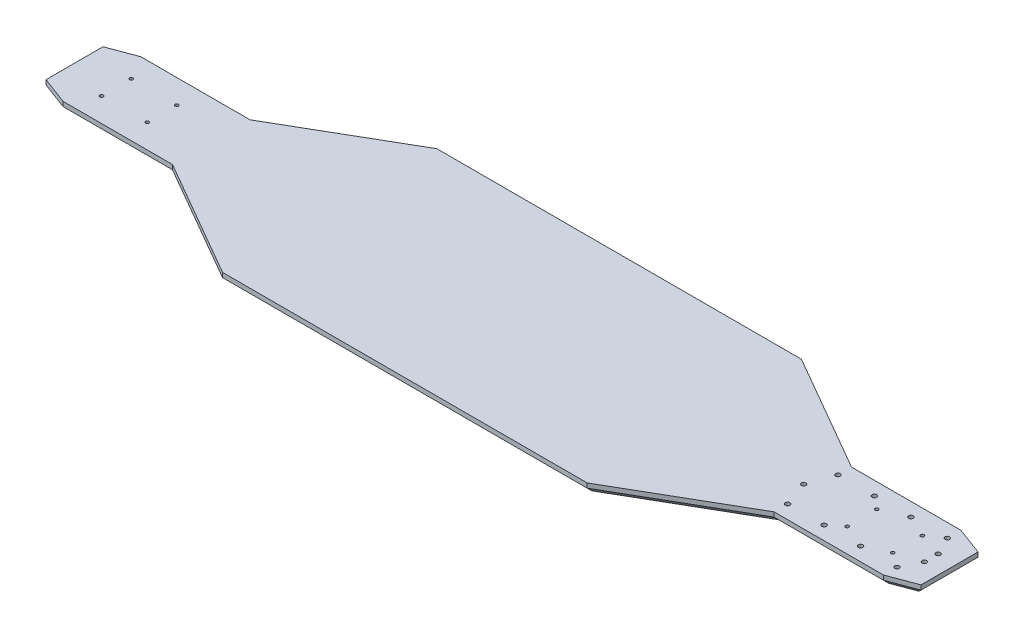
SolidWorks part; units mm, degrees
ref_plane "Front Plane" through (0, 0, 0) normal (0, 0, 1) x (1, 0, 0)
ref_plane "Top Plane" through (0, 0, 0) normal (0, 1, 0) x (1, 0, 0)
ref_plane "Right Plane" through (0, 0, 0) normal (1, 0, 0) x (0, 0, -1)
sketch "Sketch1" plane through (0, 0, 0) normal (0, 1, 0) x (1, 0, 0)
  line L0 (-241.1419, 54.734) -> (368.336, 54.734) construction
  line L1 (-241.1419, 15.0465) -> (-241.1419, 94.4215)
  line L2 (114.336, -94.491) -> (368.336, -94.491)
  line L3 (368.336, -94.491) -> (368.336, 54.734) construction
  line L4 (-50.6419, 108.709) -> (114.336, 203.959)
  line L5 (-203.0419, 108.709) -> (-241.1419, 94.4215)
  line L6 (-203.0419, 108.709) -> (-50.6419, 108.709)
  line L7 (-203.0419, 0.759) -> (-50.6419, 0.759)
  line L8 (114.336, 203.959) -> (368.336, 203.959)
  line L9 (787.3138, 0.759) -> (622.336, -94.491)
  line L10 (-203.0419, 0.759) -> (-241.1419, 15.0465)
  line L11 (-50.6419, 0.759) -> (114.336, -94.491)
  line L12 (939.7138, 0.759) -> (977.8138, 15.0465)
  line L13 (622.336, 203.959) -> (368.336, 203.959)
  line L14 (939.7138, 0.759) -> (787.3138, 0.759)
  line L15 (939.7138, 108.709) -> (787.3138, 108.709)
  line L16 (939.7138, 108.709) -> (977.8138, 94.4215)
  line L17 (787.3138, 108.709) -> (622.336, 203.959)
  line L18 (622.336, -94.491) -> (368.336, -94.491)
  line L19 (977.8138, 15.0465) -> (977.8138, 94.4215)
  dimension "D9" = 355.4778
  dimension "D2" = 149.225
  dimension "D3" = 152.4
  dimension "D4" = 38.1
  dimension "D5" = 254
  dimension "D6" = 79.375
  dimension "D7" = 150
  dimension "D8" = 14.2875
  dimension "D10" = 190.5
  dimension "D11" = 190.5
  dimension "D12" = 107.95
  dimension "D13" = 53.975
  dimension "D14" = 149.225
  dimension "D15" = 39.6875
extrude "Boss-Extrude1" add sketch "Sketch1" along normal blind 15.24
sketch "Sketch2" plane through (0, 0, 0) normal (0, -1, 0) x (-1, 0, 0)
  line L0 (241.1419, 54.734) -> (-37.1273, 54.734) construction
  line L1 (241.1419, 94.4215) -> (241.1419, 15.0465) construction
  line L2 (-368.336, -94.491) -> (-368.336, 203.959) construction
  line L3 (-114.336, -94.491) -> (-622.336, -94.491) construction
  line L4 (-622.336, 203.959) -> (-114.336, 203.959) construction
  line L5 (119.2219, 75.3715) -> (119.2219, 34.0965) construction
  line L6 (119.2219, 34.0965) -> (182.7219, 34.0965) construction
  line L7 (182.7219, 34.0965) -> (182.7219, 75.3715) construction
  line L8 (182.7219, 75.3715) -> (119.2219, 75.3715) construction
  circle A0 centre (182.7219, 34.0965) radius 2.3813
  circle A1 centre (182.7219, 75.3715) radius 2.3813
  circle A2 centre (119.2219, 75.3715) radius 2.3812
  circle A3 centre (119.2219, 34.0965) radius 2.3813
  circle A4 centre (-855.8938, 75.3715) radius 2.3813
  circle A5 centre (-919.3938, 75.3715) radius 2.3812
  circle A6 centre (-919.3938, 34.0965) radius 2.3812
  circle A7 centre (-855.8938, 34.0965) radius 2.3812
  point P29 (50.6419, 108.709)
  dimension "D1" = 58.42
  dimension "D2" = 63.5
  dimension "D3" = 41.275
  dimension "D4" = 20.6375
extrude "Cut-Extrude1" cut sketch "Sketch2" against normal blind 15.24
chamfer "Chamfer1" distance 8.89 angle 45 16 edges at (-126.8419, 0, -0.759) (-222.0919, 0, -7.9028) (-241.1419, 0, -54.734) (-222.0919, 0, -101.5653) (-126.8419, 0, -108.709) (31.8471, 0, -156.334) (31.8471, 0, 46.866) (368.336, 0, 94.491) (704.8249, 0, 46.866) (863.5138, 0, -0.759) (958.7638, 0, -7.9028) (977.8138, 0, -54.734) (958.7638, 0, -101.5653) (863.5138, 0, -108.709) (704.8249, 0, -156.334) (368.336, 0, -203.959)
sketch "Sketch3" plane through (0, 0, 0) normal (0, -1, 0) x (1, 0, 0)
  line L0 (654.086, -105.534) -> (717.586, -105.534)
  line L1 (938.1018, -9.649) -> (784.9318, -9.649) construction
  line L2 (377.861, -181.734) -> (377.861, 72.266) construction
  line L3 (419.136, -169.034) -> (419.136, 59.566)
  line L4 (114.336, 72.266) -> (114.336, -181.734) construction
  line L5 (419.136, -54.734) -> (609.636, -54.734) construction
  line L6 (514.386, -54.734) -> (514.386, -169.034) construction
  line L7 (546.136, -156.334) -> (482.636, -156.334) construction
  line L8 (546.136, -105.534) -> (482.636, -105.534) construction
  line L9 (482.636, -105.534) -> (482.636, -156.334) construction
  line L10 (631.861, -133.069) -> (631.861, 46.866) construction
  line L11 (546.136, -105.534) -> (546.136, -156.334) construction
  line L12 (654.086, -3.934) -> (717.586, -3.934)
  line L13 (654.086, -3.934) -> (654.086, -105.534)
  line L14 (717.586, -105.534) -> (717.586, -3.934)
  line L15 (609.636, -54.734) -> (792.0003, -54.734) construction
  line L16 (641.386, -123.4498) -> (641.386, 24.6279) construction
  line L17 (641.386, -118.234) -> (730.286, -118.234) construction
  line L18 (730.286, -118.234) -> (730.286, 8.766) construction
  line L19 (730.286, 8.766) -> (641.386, 8.766) construction
  line L20 (419.136, -54.734) -> (390.561, -54.734) construction
  line L21 (404.8485, -169.034) -> (404.8485, 59.566) construction
  line L22 (685.836, -118.234) -> (685.836, 8.766) construction
  line L23 (500.0985, -169.034) -> (500.0985, 59.566) construction
  line L24 (236.5735, -169.034) -> (236.5735, 59.566) construction
  line L25 (50.836, -118.234) -> (50.836, 8.766) construction
  line L26 (331.8235, -169.034) -> (331.8235, 59.566) construction
  line L27 (317.536, -54.734) -> (346.111, -54.734) construction
  line L28 (6.386, 8.766) -> (95.286, 8.766) construction
  line L29 (6.386, -118.234) -> (6.386, 8.766) construction
  line L30 (95.286, -118.234) -> (6.386, -118.234) construction
  line L31 (95.286, -123.4498) -> (95.286, 24.6279) construction
  line L32 (127.036, -54.734) -> (-55.3283, -54.734) construction
  line L33 (190.536, -105.534) -> (190.536, -156.334) construction
  line L34 (104.811, -133.069) -> (104.811, 46.866) construction
  line L35 (254.036, -105.534) -> (254.036, -156.334) construction
  line L36 (190.536, -105.534) -> (254.036, -105.534) construction
  line L37 (368.336, -181.734) -> (368.336, 72.266) construction
  line L38 (190.536, -156.334) -> (254.036, -156.334) construction
  line L39 (222.286, -54.734) -> (222.286, -169.034) construction
  line L40 (622.336, 72.266) -> (622.336, -181.734) construction
  line L41 (317.536, -54.734) -> (127.036, -54.734) construction
  line L42 (358.811, -181.734) -> (358.811, 72.266) construction
  line L43 (-44.6867, -22.984) -> (120.2912, 72.266)
  line L44 (-199.8669, -22.984) -> (-44.6867, -22.984)
  line L45 (609.636, -169.034) -> (390.561, -169.034)
  line L46 (609.636, -169.034) -> (609.636, 59.566)
  line L47 (609.636, 59.566) -> (390.561, 59.566)
  line L48 (390.561, -169.034) -> (390.561, 59.566)
  line L49 (-218.9169, -30.4485) -> (-199.8669, -22.984)
  line L50 (-218.9169, -79.0196) -> (-218.9169, -30.4485)
  line L51 (-199.0117, -86.484) -> (-218.9169, -79.0196)
  line L52 (-44.6867, -86.484) -> (-199.0117, -86.484)
  line L53 (120.2912, -181.734) -> (-44.6867, -86.484)
  line L54 (346.111, -169.034) -> (346.111, 59.566)
  line L55 (127.036, 59.566) -> (346.111, 59.566)
  line L56 (127.036, -169.034) -> (127.036, 59.566)
  line L57 (127.036, -169.034) -> (346.111, -169.034)
  line L58 (19.086, -105.534) -> (19.086, -3.934)
  line L59 (82.586, -3.934) -> (82.586, -105.534)
  line L60 (82.586, -3.934) -> (19.086, -3.934)
  line L61 (317.536, -169.034) -> (317.536, 59.566)
  line L62 (82.586, -105.534) -> (19.086, -105.534)
  line L63 (955.5888, -79.0196) -> (936.5388, -79.0196) construction
  line L64 (936.5388, -79.0196) -> (936.5388, -30.4485) construction
  line L65 (936.5388, -30.4485) -> (955.5888, -30.4485) construction
  line L66 (968.9238, -88.2607) -> (968.9238, -21.2073) construction
  line L76 (616.3808, -181.734) -> (781.3587, -86.484)
  line L77 (781.3587, -86.484) -> (935.6837, -86.484)
  line L78 (935.6837, -86.484) -> (955.5888, -79.0196)
  line L79 (955.5888, -79.0196) -> (955.5888, -30.4485)
  line L80 (955.5888, -30.4485) -> (936.5388, -22.984)
  line L81 (936.5388, -22.984) -> (781.3587, -22.984)
  line L82 (781.3587, -22.984) -> (616.3808, 72.266)
  circle A0 centre (358.811, 46.866) radius 3.175
  circle A1 centre (546.136, -156.334) radius 3.175
  circle A2 centre (482.636, -156.334) radius 3.175
  circle A4 centre (546.136, -105.534) radius 3.175
  circle A5 centre (358.811, -3.934) radius 3.175
  circle A6 centre (482.636, -105.534) radius 3.175
  circle A7 centre (546.136, -80.134) radius 3.175
  circle A8 centre (546.136, -29.334) radius 3.175
  circle A9 centre (482.636, -29.334) radius 3.175
  circle A10 centre (482.636, -80.134) radius 3.175
  circle A11 centre (546.136, -3.934) radius 3.175
  circle A12 centre (546.136, 46.866) radius 3.175
  circle A13 centre (482.636, 46.866) radius 3.175
  circle A14 centre (482.636, -3.934) radius 3.175
  circle A15 centre (730.286, -54.734) radius 3.175
  circle A16 centre (730.286, -105.534) radius 3.175
  circle A17 centre (730.286, -3.934) radius 3.175
  circle A18 centre (711.236, 8.766) radius 3.175
  circle A19 centre (660.436, 8.766) radius 3.175
  circle A20 centre (622.336, -156.334) radius 3.175
  circle A21 centre (404.8485, -156.334) radius 3.175
  circle A22 centre (404.8485, -105.534) radius 3.175
  circle A23 centre (404.8485, -54.734) radius 3.175
  circle A24 centre (404.8485, -3.934) radius 3.175
  circle A25 centre (404.8485, 46.866) radius 3.175
  circle A26 centre (660.436, -118.234) radius 3.175
  circle A27 centre (711.236, -118.234) radius 3.175
  circle A28 centre (641.386, -105.534) radius 3.175
  circle A29 centre (641.386, -54.734) radius 3.175
  circle A30 centre (641.386, -3.934) radius 3.175
  circle A31 centre (622.336, -105.534) radius 3.175
  circle A32 centre (622.336, -54.734) radius 3.175
  circle A33 centre (622.336, -3.934) radius 3.175
  circle A34 centre (622.336, 46.866) radius 3.175
  circle A35 centre (601.6985, -181.734) radius 3.175
  circle A36 centre (550.8985, -181.734) radius 3.175
  circle A37 centre (500.0985, -181.734) radius 3.175
  circle A38 centre (449.2985, -181.734) radius 3.175
  circle A39 centre (398.4985, -181.734) radius 3.175
  circle A40 centre (398.4985, 72.266) radius 3.175
  circle A41 centre (449.2985, 72.266) radius 3.175
  circle A42 centre (500.0985, 72.266) radius 3.175
  circle A43 centre (550.8985, 72.266) radius 3.175
  circle A44 centre (601.6985, 72.266) radius 3.175
  circle A45 centre (377.861, -156.334) radius 3.175
  circle A46 centre (377.861, -105.534) radius 3.175
  circle A47 centre (377.861, -54.734) radius 3.175
  circle A48 centre (377.861, -3.934) radius 3.175
  circle A49 centre (377.861, 46.866) radius 3.175
  circle A50 centre (358.811, -54.734) radius 3.175
  circle A51 centre (358.811, -105.534) radius 3.175
  circle A52 centre (358.811, -156.334) radius 3.175
  circle A53 centre (134.9735, 72.266) radius 3.175
  circle A54 centre (185.7735, 72.266) radius 3.175
  circle A55 centre (236.5735, 72.266) radius 3.175
  circle A56 centre (287.3735, 72.266) radius 3.175
  circle A57 centre (338.1735, 72.266) radius 3.175
  circle A58 centre (338.1735, -181.734) radius 3.175
  circle A59 centre (287.3735, -181.734) radius 3.175
  circle A60 centre (236.5735, -181.734) radius 3.175
  circle A61 centre (185.7735, -181.734) radius 3.175
  circle A62 centre (134.9735, -181.734) radius 3.175
  circle A63 centre (114.336, 46.866) radius 3.175
  circle A64 centre (114.336, -3.934) radius 3.175
  circle A65 centre (114.336, -54.734) radius 3.175
  circle A66 centre (114.336, -105.534) radius 3.175
  circle A67 centre (95.286, -3.934) radius 3.175
  circle A68 centre (95.286, -54.734) radius 3.175
  circle A69 centre (95.286, -105.534) radius 3.175
  circle A70 centre (25.436, -118.234) radius 3.175
  circle A71 centre (76.236, -118.234) radius 3.175
  circle A72 centre (331.8235, 46.866) radius 3.175
  circle A73 centre (331.8235, -3.934) radius 3.175
  circle A74 centre (331.8235, -54.734) radius 3.175
  circle A75 centre (331.8235, -105.534) radius 3.175
  circle A76 centre (331.8235, -156.334) radius 3.175
  circle A77 centre (114.336, -156.334) radius 3.175
  circle A78 centre (76.236, 8.766) radius 3.175
  circle A79 centre (25.436, 8.766) radius 3.175
  circle A80 centre (6.386, -3.934) radius 3.175
  circle A81 centre (6.386, -105.534) radius 3.175
  circle A82 centre (6.386, -54.734) radius 3.175
  circle A83 centre (254.036, -3.934) radius 3.175
  circle A84 centre (254.036, 46.866) radius 3.175
  circle A85 centre (190.536, 46.866) radius 3.175
  circle A86 centre (190.536, -3.934) radius 3.175
  circle A87 centre (254.036, -80.134) radius 3.175
  circle A88 centre (254.036, -29.334) radius 3.175
  circle A89 centre (190.536, -29.334) radius 3.175
  circle A90 centre (190.536, -80.134) radius 3.175
  circle A91 centre (254.036, -105.534) radius 3.175
  circle A92 centre (190.536, -105.534) radius 3.175
  circle A93 centre (254.036, -156.334) radius 3.175
  circle A94 centre (190.536, -156.334) radius 3.175
  circle A95 centre (0, 0) radius 2.7305
  circle A99 centre (-218.9169, -79.0196) radius 2.7305
  circle A100 centre (-199.8669, -79.0196) radius 2.7305
  circle A101 centre (-199.8669, -30.4485) radius 2.7305
  circle A102 centre (-218.9169, -30.4485) radius 2.7305
  circle A103 centre (936.5388, -29.334) radius 3.175
  circle A104 centre (936.5388, -80.134) radius 3.175
  circle A105 centre (955.5888, -80.134) radius 3.175
  circle A106 centre (955.5888, -29.334) radius 3.175
  point P48 (114.336, -203.959)
  point P276 (114.336, 94.491)
  point P302 (955.5888, -54.734)
  dimension "D7" = 6.35
  dimension "D13" = 31.75
  dimension "D20" = 3
  dimension "D39" = 5
  dimension "D5" = 6.35
  dimension "D8" = 6.35
  dimension "D11" = 6.35
  dimension "D12" = 6.35
  dimension "D14" = 50.8
  dimension "D15" = 25.4
  dimension "D43" = 6.35
  dimension "D44" = 6.35
  dimension "D45" = 6.35
  dimension "D46" = 6.35
  dimension "D47" = 6.35
  dimension "D48" = 6.35
  dimension "D49" = 6.35
  dimension "D50" = 6.35
  dimension "D51" = 6.35
  dimension "D52" = 6.35
  dimension "D53" = 6.35
  dimension "D54" = 6.35
  dimension "D3" = 254
  dimension "D6" = 9.525
  dimension "D9" = 219.075
  dimension "D10" = 190.5
  dimension "D16" = 31.75
  dimension "D17" = 13.335
  dimension "D18" = 12.7
  dimension "D19" = 50.8
  dimension "D21" = 12.7
  dimension "D22" = 101.6
  dimension "D23" = 63.5
  dimension "D24" = 22.225
  dimension "D25" = 12.7
  dimension "D26" = 50.8
  dimension "D27" = 12.7
  dimension "D28" = 12.7
  dimension "D29" = 12.7
  dimension "D30" = 19.05
  dimension "D31" = 50.8
  dimension "D32" = 50.8
  dimension "D33" = 50.8
  dimension "D34" = 12.7
  dimension "D35" = 25.4
  dimension "D36" = 20.6375
  dimension "D37" = 25.4
  dimension "D38" = 5
  dimension "D41" = 19.05
  dimension "D42" = 13.335
  dimension "D40" = 5
extrude "Cut-Extrude2" cut sketch "Sketch3" against normal blind 7.9375
sketch "Sketch4" plane through (0, 15.24, 0) normal (0, 1, 0) x (1, 0, 0)
  line L0 (977.8138, 15.0465) -> (977.8138, 94.4215) construction
  line L1 (977.8138, 89.659) -> (774.6138, 89.659)
  line L2 (977.8138, 89.659) -> (977.8138, 19.809)
  line L3 (977.8138, 19.809) -> (774.6138, 19.809)
  line L4 (774.6138, 89.659) -> (774.6138, 19.809)
  line L5 (952.4138, 89.659) -> (952.4138, 19.809) construction
  line L6 (774.6138, 54.734) -> (977.8138, 54.734) construction
  circle A0 centre (888.9138, 89.7619) radius 3.175
  circle A1 centre (952.4138, 45.209) radius 3.175
  circle A2 centre (939.7138, 89.7619) radius 3.175
  circle A3 centre (939.7138, 19.7061) radius 3.175
  circle A4 centre (888.9138, 19.7061) radius 3.175
  circle A5 centre (838.1138, 19.7061) radius 3.175
  circle A6 centre (838.1138, 89.7619) radius 3.175
  circle A7 centre (774.6138, 54.734) radius 3.175
  circle A8 centre (787.3138, 89.7619) radius 3.175
  circle A9 centre (952.4138, 64.259) radius 3.175
  circle A10 centre (787.3138, 19.7061) radius 3.175
  dimension "D6" = 6.35
  dimension "D7" = 6.35
  dimension "D11" = 6.35
  dimension "D1" = 69.85
  dimension "D2" = 203.2
  dimension "D3" = 4.7625
  dimension "D4" = 25.4
  dimension "D5" = 25.4
  dimension "D8" = 38.1
  dimension "D10" = 12.7
  dimension "D9" = 4
extrude "Cut-Extrude3" cut sketch "Sketch4" against normal blind 7.9375
